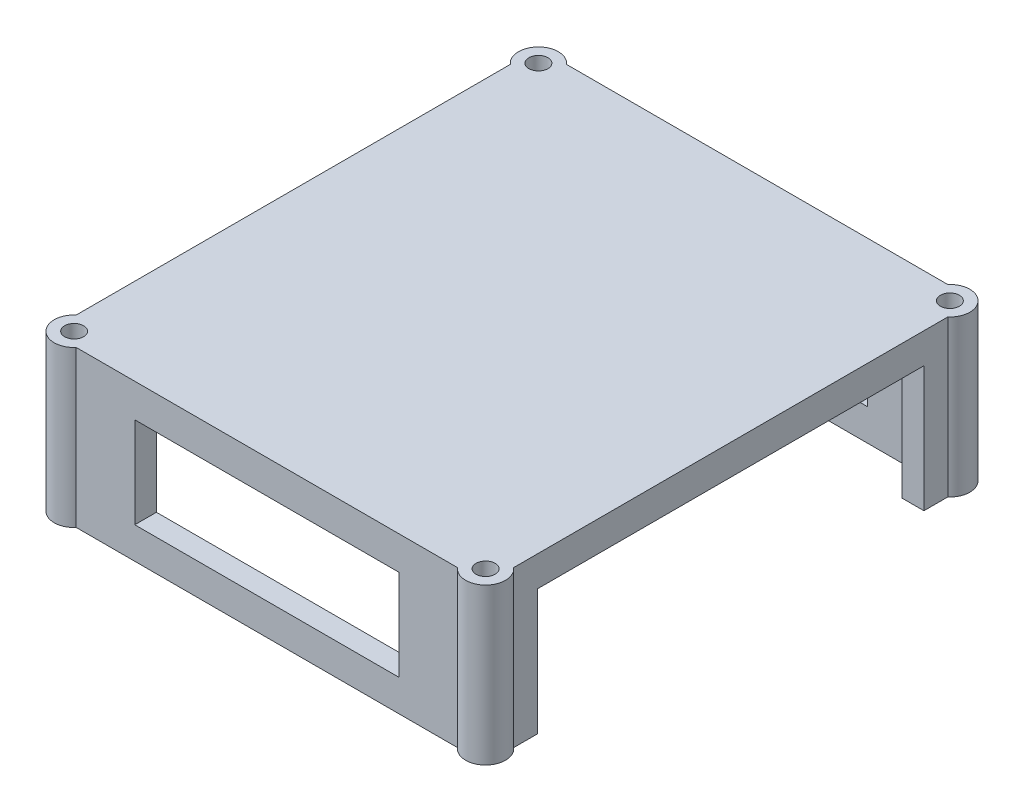
SolidWorks part; units mm, degrees
ref_plane "Front Plane" through (0, 0, 0) normal (0, 0, 1) x (1, 0, 0)
ref_plane "Top Plane" through (0, 0, 0) normal (0, 1, 0) x (1, 0, 0)
ref_plane "Right Plane" through (0, 0, 0) normal (1, 0, 0) x (0, 0, -1)
sketch "Sketch1" plane through (0, 0, 0) normal (0, 1, 0) x (1, 0, 0)
  line L1 (0, 0) -> (128.27, 0)
  line L2 (0, 0) -> (0, 143.764)
  line L3 (0, 143.764) -> (128.27, 143.764)
  line L4 (128.27, 0) -> (128.27, 143.764)
  dimension "D1" = 128.27
  dimension "D2" = 143.764
extrude "Boss-Extrude1" add sketch "Sketch1" along normal blind 45.72
sketch "Sketch3" plane through (0, 0, 0) normal (0, -1, 0) x (1, 0, 0)
  line L0 (0, -143.764) -> (0, 0) construction
  line L1 (6.35, -6.35) -> (121.92, -6.35)
  line L2 (6.35, -6.35) -> (6.35, -137.414)
  line L3 (6.35, -137.414) -> (121.92, -137.414)
  line L4 (121.92, -6.35) -> (121.92, -137.414)
  line L5 (0, 0) -> (128.27, 0) construction
  line L6 (128.27, -143.764) -> (0, -143.764) construction
  dimension "D1" = 115.57
  dimension "D2" = 6.35
  dimension "D3" = 6.35
  dimension "D4" = 6.35
extrude "Cut-Extrude1" cut sketch "Sketch3" against normal blind 41.91
sketch "Sketch4" plane through (0, 0, -143.764) normal (0, 0, -1) x (-1, 0, 0)
  line L0 (-128.27, 0) -> (0, 0) construction
  line L1 (-102.87, 35.941) -> (-25.4, 35.941)
  line L2 (-102.87, 35.941) -> (-102.87, 9.271)
  line L3 (-102.87, 9.271) -> (-25.4, 9.271)
  line L4 (-25.4, 35.941) -> (-25.4, 9.271)
  line L7 (-128.27, 45.72) -> (-128.27, 0) construction
  dimension "D1" = 26.67
  dimension "D2" = 77.47
  dimension "D3" = 9.271
  dimension "D4" = 25.4
extrude "Cut-Extrude2" cut sketch "Sketch4" against normal blind 190.754
sketch "Sketch5" plane through (128.27, 0, 0) normal (1, 0, 0) x (0, 0, -1)
  line L0 (0, 45.72) -> (143.764, 45.72) construction
  line L1 (15.24, 36.83) -> (128.524, 36.83)
  line L2 (15.24, 36.83) -> (15.24, -10.16)
  line L3 (15.24, -10.16) -> (128.524, -10.16)
  line L4 (128.524, 36.83) -> (128.524, -10.16)
  line L6 (0, 45.72) -> (0, 0) construction
  dimension "D1" = 46.99
  dimension "D2" = 113.284
  dimension "D3" = 8.89
  dimension "D4" = 15.24
extrude "Cut-Extrude3" cut sketch "Sketch5" against normal blind 190.754 contours L2 L1 L4 L3
sketch "Sketch6" plane through (0, 0, 0) normal (0, -1, 0) x (-1, 0, 0)
  line L0 (0, 0) -> (-128.27, 0) construction
  line L1 (0, 15.24) -> (0, 0) construction
  line L2 (-128.27, 0) -> (-128.27, 15.24) construction
  line L3 (-128.27, 143.764) -> (0, 143.764) construction
  line L4 (0, 143.764) -> (0, 128.524) construction
  line L5 (-128.27, 128.524) -> (-128.27, 143.764) construction
  circle A0 centre (-3.81, 3.81) radius 2.794
  circle A1 centre (-124.46, 3.81) radius 2.794
  circle A2 centre (-3.81, 139.954) radius 2.794
  circle A3 centre (-124.46, 139.954) radius 2.794
  dimension "D1" = 5.588
  dimension "D2" = 5.588
  dimension "D3" = 5.588
  dimension "D4" = 5.588
  dimension "D6" = 3.81
  dimension "D7" = 3.81
  dimension "D8" = 3.81
  dimension "D9" = 3.81
  dimension "D10" = 3.81
  dimension "D11" = 3.81
  dimension "D12" = 3.81
  dimension "D5" = 3.81
extrude "Cut-Extrude4" cut sketch "Sketch6" against normal through all
ref_plane "Plane1" through (64.135, 0, 0) normal (1, 0, 0) x (0, 0, -1)
ref_plane "Plane4" through (0, 0, -71.882) normal (0, 0, -1) x (-1, 0, 0)
sketch "Sketch7" plane through (0, 0, 0) normal (0, -1, 0) x (1, 0, 0)
  circle A0 centre (3.81, -3.81) radius 2.794
  circle A1 centre (3.81, -3.81) radius 5.842
  circle A2 centre (3.81, -3.81) radius 2.794 construction
  dimension "D1" = 3.048
extrude "Boss-Extrude2" add sketch "Sketch7" against normal through all
sketch "Sketch8" plane through (0, 0, 0) normal (0, -1, 0) x (1, 0, 0)
  circle A0 centre (124.46, -3.81) radius 2.794
  circle A1 centre (124.46, -3.81) radius 5.842
  circle A2 centre (124.46, -3.81) radius 2.794 construction
  dimension "D1" = 3.048
extrude "Boss-Extrude3" add sketch "Sketch8" against normal through all
sketch "Sketch9" plane through (0, 0, 0) normal (0, -1, 0) x (1, 0, 0)
  circle A0 centre (3.81, -139.954) radius 2.794
  circle A1 centre (3.81, -139.954) radius 5.842
  circle A2 centre (3.81, -139.954) radius 2.794 construction
  dimension "D1" = 3.048
extrude "Boss-Extrude4" add sketch "Sketch9" against normal through all
sketch "Sketch10" plane through (0, 0, 0) normal (0, -1, 0) x (1, 0, 0)
  circle A0 centre (124.46, -139.954) radius 2.794
  circle A1 centre (124.46, -139.954) radius 5.842
  circle A2 centre (124.46, -139.954) radius 2.794 construction
  dimension "D1" = 3.048
extrude "Boss-Extrude5" add sketch "Sketch10" against normal through all
